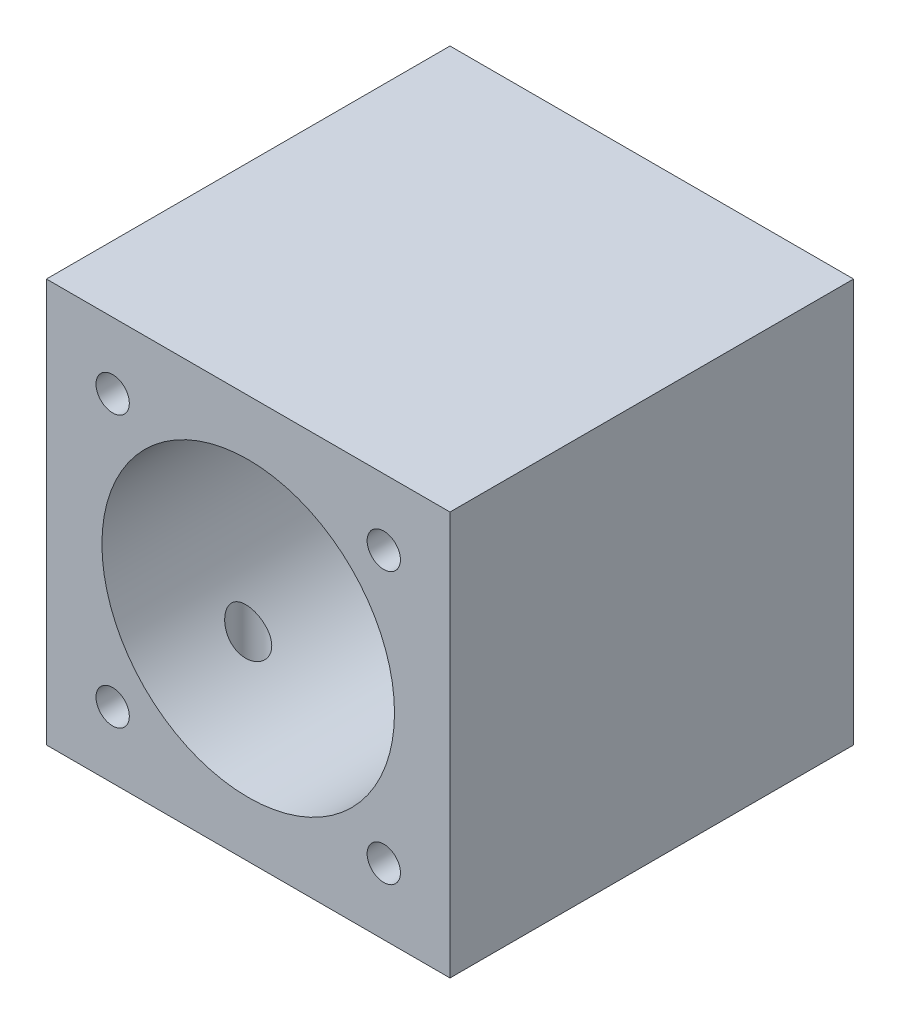
SolidWorks part; units mm, degrees
ref_plane "Front Plane" through (0, 0, 0) normal (0, 0, 1) x (1, 0, 0)
ref_plane "Top Plane" through (0, 0, 0) normal (0, 1, 0) x (1, 0, 0)
ref_plane "Right Plane" through (0, 0, 0) normal (1, 0, 0) x (0, 0, -1)
sketch "Sketch1" plane through (0, 0, 0) normal (0, 0, 1) x (1, 0, 0)
  line L1 (20, -20) -> (-20, -20)
  line L2 (20, -20) -> (20, 20)
  line L3 (20, 20) -> (-20, 20)
  line L4 (-20, -20) -> (-20, 20)
  line L5 (20, -20) -> (-20, 20) construction
  line L6 (20, 20) -> (-20, -20) construction
  circle A0 centre (0, 0) radius 14.5
  point P0 (0, 0)
  dimension "D3" = 29
  dimension "D1" = 40
  dimension "D2" = 40
extrude "Boss-Extrude1" add sketch "Sketch1" along normal blind 40
sketch "Sketch2" plane through (0, 0, 40) normal (0, 0, 1) x (1, 0, 0)
  line L0 (-20, -20) -> (20, 20) construction
  line L1 (0, 0) -> (20, 0) construction
  line L2 (20, -20) -> (20, 20) construction
  line L3 (-20, 20) -> (20, -20) construction
  circle A0 centre (0, 0) radius 19 construction
  dimension "D1" = 38
hole_wizard "M4 Tapped Hole1" positions "3DSketch1" profile "Sketch3" tap size "M4" standard "ISO"
sketch3d "3DSketch1"
  line L0 (-20, 20, 40) -> (20, -20, 40) construction
  line L1 (-20, -20, 40) -> (20, 20, 40) construction
  circle A0 centre (0, 0, 40) radius 19 construction
  point P0 (-13.435, 13.435, 40)
  point P6 (0, 0, 59)
  point P7 (13.435, 13.435, 40)
  point P11 (13.435, -13.435, 40)
  point P13 (-13.435, -13.435, 40)
sketch "Sketch3" plane through (-13.435, 13.435, 40) normal (1, 0, 0) x (0, -1, 0)
  line L0 (0, 0) -> (0, 17.0914)
  line L1 (0, 17.0914) -> (1.65, 16.1)
  line L2 (1.65, 16.1) -> (1.65, 0)
  line L5 (1.65, 0) -> (0, 0)
  line L10 (0, 17.0914) -> (-1.65, 16.1) construction
  line L11 (0, -6.35) -> (0, 107.95) construction
  dimension "Tap Drill Dia." = 3.3
  dimension "Tap Drill Depth" = 16.1
  dimension "Drill Angle" = 118
sketch "Sketch4" plane through (0, -20, 0) normal (0, -1, 0) x (1, 0, 0)
  line L0 (-20, 20) -> (20, 20) construction
  line L1 (-20, 40) -> (-20, 0) construction
  line L2 (20, 40) -> (20, 0) construction
  line L3 (0, 40) -> (0, 0) construction
  line L4 (19, 40) -> (-19, 40) construction
  point P11 (-10, 30)
  point P12 (10, 30)
  point P13 (10, 10)
  point P14 (-10, 10)
  dimension "D1" = 10
  dimension "D2" = 10
hole_wizard "M4 Tapped Hole2" positions "3DSketch2" profile "Sketch5" tap size "M4" standard "ISO"
sketch3d "3DSketch2"
  point P0 (-10, -20, 30)
  point P3 (10, -20, 30)
  point P6 (10, -20, 10)
  point P9 (-10, -20, 10)
sketch "Sketch5" plane through (-10, -20, 30) normal (1, 0, 0) x (0, 0, -1)
  line L0 (0, 0) -> (0, 17.0914)
  line L1 (0, 17.0914) -> (1.65, 16.1)
  line L2 (1.65, 16.1) -> (1.65, 0)
  line L5 (1.65, 0) -> (0, 0)
  line L10 (0, 17.0914) -> (-1.65, 16.1) construction
  line L11 (0, -6.35) -> (0, 107.95) construction
  dimension "Tap Drill Dia." = 3.3
  dimension "Tap Drill Depth" = 16.1
  dimension "Drill Angle" = 118
